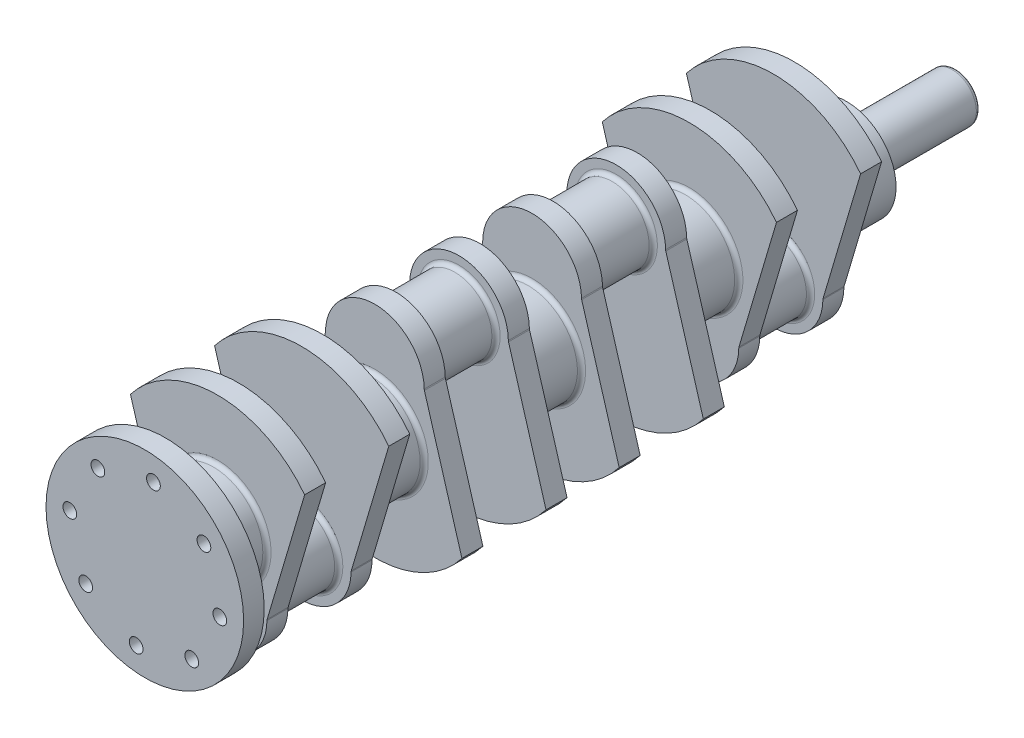
SolidWorks part; units mm, degrees
ref_plane "Front Plane" through (0, 0, 0) normal (0, 0, 1) x (1, 0, 0)
ref_plane "Top Plane" through (0, 0, 0) normal (0, 1, 0) x (1, 0, 0)
ref_plane "Right Plane" through (0, 0, 0) normal (1, 0, 0) x (0, 0, -1)
sketch "Sketch1" plane through (0, 0, 0) normal (0, 0, 1) x (1, 0, 0)
  line L0 (0, 56.2084) -> (0, -44) construction
  line L1 (-89.355, 0) -> (71.0373, 0) construction
  line L2 (-36, -44) -> (-63.4618, 48.7094)
  line L3 (36, -44) -> (63.4618, 48.7094)
  circle A0 centre (0, -44) radius 36
  arc A1 (-63.4618, 48.7094) -> (63.4618, 48.7094) centre (0, 0) cw
  dimension "D1" = 72
  dimension "D2" = 33
  dimension "D3" = 80
  dimension "D4" = 44
extrude "Boss-Extrude1" add sketch "Sketch1" along normal blind 15.3005 contours A1 L2 A0 L3 | A0 L2
sketch "Sketch2" plane through (0, 0, 15.3005) normal (0, 0, 1) x (1, 0, 0)
  circle A1 centre (0, -44) radius 27
extrude "Boss-Extrude2" add sketch "Sketch2" along normal blind 46
sketch "Sketch3" plane through (0, 0, 0) normal (0, 0, -1) x (-1, 0, 0)
  circle A0 centre (0, 0) radius 36
  dimension "D1" = 72
extrude "Boss-Extrude3" add sketch "Sketch3" along normal blind 38
ref_plane "Plane1" through (0, 0, 38.3005) normal (0, 0, 1) x (1, 0, 0)
mirror "Mirror1" about plane through (0, 0, 38.3005) normal (0, 0, 1) of "Boss-Extrude1", "Boss-Extrude3"
ref_plane "Plane2" through (0, 0, 95.6011) normal (0, 0, 1) x (1, 0, 0)
mirror "Mirror8" about plane through (0, 0, 95.6011) normal (0, 0, 1) of bodies 107
move or copy body "Body-Move/Copy3" bodies to move or copy 115 copy no rotation origin (0, 0, 0) rotation axis (0, 0, 1) rotation angle 180
ref_plane "Plane3" through (0, 0, 210.2021) normal (0, 0, 1) x (1, 0, 0)
mirror "Mirror9" about plane through (0, 0, 210.2021) normal (0, 0, 1) of bodies 107 116
sketch "Sketch4" plane through (0, 0, -38) normal (0, 0, -1) x (-1, 0, 0)
  circle A0 centre (0, 0) radius 17.5
extrude "Boss-Extrude4" add sketch "Sketch4" along normal blind 80
sketch "Sketch5" plane through (0, 0, 458.4042) normal (0, 0, 1) x (1, 0, 0)
  circle A0 centre (0, 0) radius 72
  circle A1 centre (0, 0) radius 55 construction
  circle A2 centre (6.2849, 54.6397) radius 5
  circle A3 centre (43.0802, 34.1921) radius 5
  circle A4 centre (54.6397, -6.2849) radius 5
  circle A5 centre (34.1921, -43.0802) radius 5
  circle A6 centre (-6.2849, -54.6397) radius 5
  circle A7 centre (-43.0802, -34.1921) radius 5
  circle A8 centre (-54.6397, 6.2849) radius 5
  circle A9 centre (-34.1921, 43.0802) radius 5
  point P23 (0, 0)
  dimension "D1" = 8
extrude "Boss-Extrude6" add sketch "Sketch5" along normal blind 15
combine bodies "Combine1" operation type add bodies to combine 119 116 118 121
fillet "Fillet1" radius 3 35 edges at (27, -44, 15.3005) (27, -44, 61.3005) (-36, 0, 0) (36, -44, 68.9508) (-36, -44, 68.9508) (-36, 0, 76.6011) (-17.5, 0, -38) (-17.5, 0, -118) (36, 44, 183.5519) (-36, 44, 183.5519) (-27, 44, 175.9016) (36, 0, 191.2021) (-27, 44, 129.9016) (36, 0, 229.2021) (-36, 44, 122.2513) (36, 44, 122.2513) (36, 0, 114.6011) (36, 44, 236.8524) (-36, 44, 236.8524) (-27, 44, 244.5027) (-36, 44, 298.1529) (36, 44, 298.1529) (-27, 44, 290.5027) (36, 0, 305.8032) (-36, 0, 343.8032) (-36, -44, 412.754) (36, -44, 412.754) (27, -44, 405.1037) (-36, 0, 420.4042) (27, -44, 359.1037) (-36, 0, 458.4042) (36, -44, 351.4535) (-36, -44, 351.4535) (36, -44, 7.6503) (-36, -44, 7.6503)
